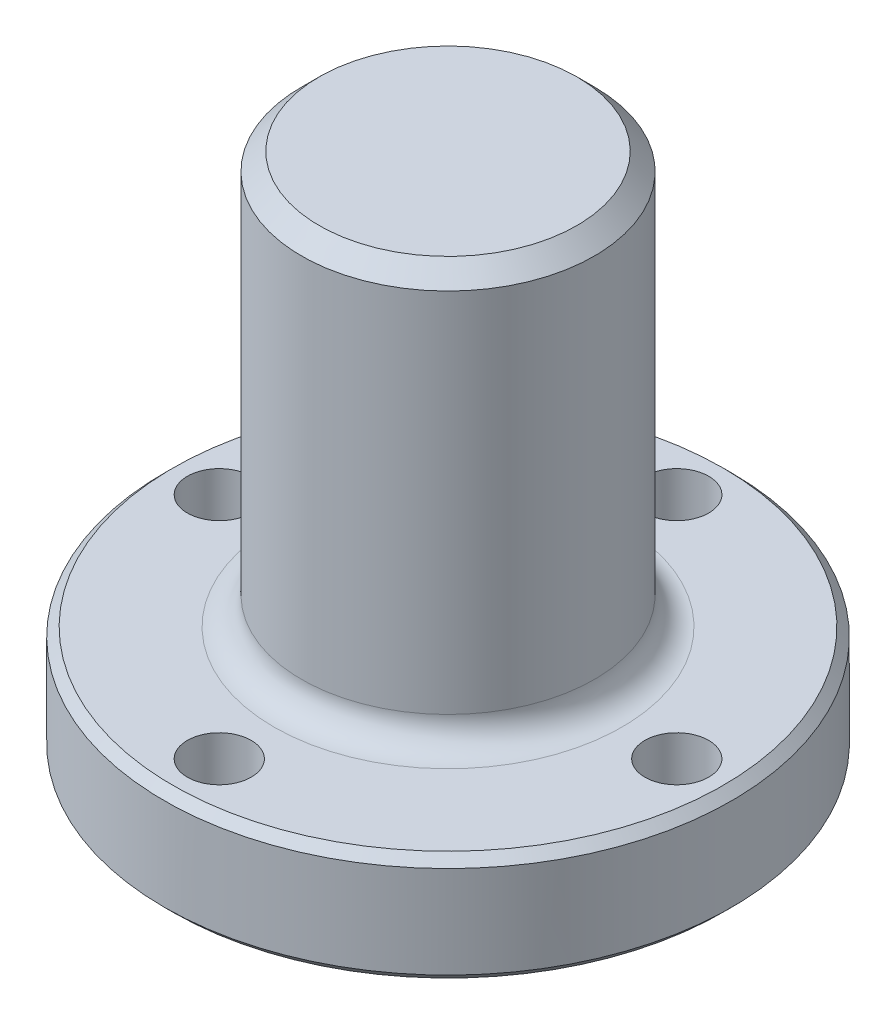
SolidWorks part; units mm, degrees
ref_plane "Front Plane" through (0, 0, 0) normal (1, 0, 0) x (0, 1, 0)
ref_plane "Top Plane" through (0, 0, 0) normal (0, 0, 1) x (0, 1, 0)
ref_plane "Right Plane" through (0, 0, 0) normal (0, 1, 0) x (-1, 0, 0)
sketch "Sketch1" plane through (0, 0, 0) normal (0, 0, 1) x (0, 1, 0)
  line L0 (-25.0317, 0) -> (-25.0317, 8.7122)
  line L1 (-25.0317, 8.7122) -> (-20.2057, 8.7122)
  line L2 (-20.2057, 8.7122) -> (-20.2057, 24.6126)
  line L3 (-20.2057, 24.6126) -> (-10.6807, 24.6126)
  line L4 (-10.6807, 24.6126) -> (-10.6807, 12.7)
  line L5 (-10.6807, 12.7) -> (25.0317, 12.7)
  line L6 (25.0317, 12.7) -> (25.0317, 0)
  line L7 (25.0317, 0) -> (-25.0317, 0)
  line L8 (-50.4317, 0) -> (50.4317, 0) construction
revolve "Revolve1" add sketch "Sketch1" angle 360 about L8
sketch "Sketch2" plane through (0, 0, 0) normal (0, 1, 0) x (-1, 0, 0)
  circle A0 centre (19.8374, 0) radius 2.7686
extrude "Cut-Extrude2" cut sketch "Sketch2" along normal up to next from offset 20.2057
sketch "Sketch3" plane through (0, 0, 0) normal (0, 1, 0) x (-1, 0, 0)
  circle A0 centre (0, 19.8374) radius 2.7686
  circle A1 centre (-19.8374, 0) radius 2.7686
  circle A2 centre (0, -19.8374) radius 2.7686
extrude "Cut-Extrude4" cut sketch "Sketch3" along normal up to next from offset 20.2057
fillet "Fillet1" radius 2.3876 1 edges at (0, -10.6807, -12.7)
chamfer "Chamfer1" distance 0.762 angle 45 2 edges at (0, -10.6807, -24.6126) (0, -20.2057, -24.6126)
chamfer "Chamfer2" distance 1.524 angle 45 1 edges at (0, 25.0317, -12.7)
